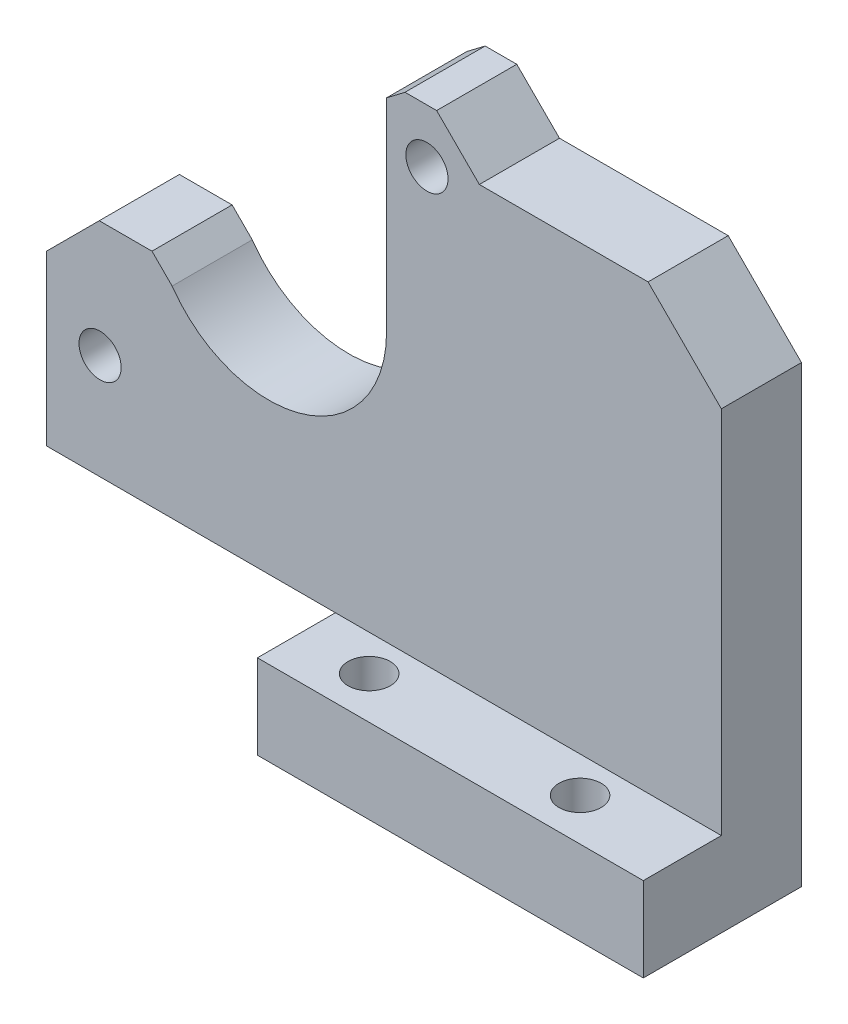
SolidWorks part; units mm, degrees
material "ABS"
ref_plane "Front Plane" through (0, 0, 0) normal (0, 0, 1) x (1, 0, 0)
ref_plane "Top Plane" through (0, 0, 0) normal (0, 1, 0) x (1, 0, 0)
ref_plane "Right Plane" through (0, 0, 0) normal (1, 0, 0) x (0, 0, -1)
sketch "Sketch1" plane through (0, 0, 0) normal (0, 0, 1) x (1, 0, 0)
  line L3 (57.05, 42) -> (41.05, 42)
  line L4 (41.05, 42) -> (37, 46.05)
  line L5 (37, 46.05) -> (34, 46.05)
  line L6 (34, 46.05) -> (32.25, 44.7181)
  line L7 (32.25, 44.7181) -> (32.25, 25.4681)
  line L8 (11.91, 19.09) -> (10, 21)
  line L9 (10, 21) -> (5, 21)
  line L10 (5, 21) -> (0, 16)
  line L14 (0, 0) -> (0, 16)
  line L21 (64, -8) -> (64, 35.05)
  line L22 (57.05, 42) -> (64, 35.05)
  line L26 (0, 0) -> (27.4, 0)
  line L27 (27.4, 0) -> (27.4, -8)
  line L28 (27.4, -8) -> (64, -8)
  arc A0 (32.25, 25.4681) -> (11.91, 19.09) centre (21.08, 25.4681) cw
  dimension "D11" = 5
  dimension "D8" = 21.08
  dimension "D16" = 11.17
  dimension "D2" = 16
  dimension "D3" = 5
  dimension "D4" = 5
  dimension "D5" = 3
  dimension "D6" = 19.25
  dimension "D7" = 8
  dimension "D9" = 6.95
  dimension "D10" = 16
  dimension "D12" = 4.05
  dimension "D13" = 27.4
  dimension "D14" = 36.6
  dimension "D15" = 50
  dimension "D17" = 1.91
  dimension "D18" = 6.95
  dimension "D19" = 4.05
  dimension "D20" = 1.91
extrude "Boss-Extrude1" add sketch "Sketch1" along normal blind 7.6
sketch "Sketch2" plane through (0, 0, 7.6) normal (0, 0, 1) x (1, 0, 0)
  line L1 (64, 0) -> (27.4, 0)
  line L2 (64, 0) -> (64, -8)
  line L3 (64, -8) -> (27.4, -8)
  line L4 (27.4, 0) -> (27.4, -8)
  dimension "D1" = 8
extrude "Boss-Extrude2" add sketch "Sketch2" along normal blind 7.4
sketch "Sketch3" plane through (0, 0, 0) normal (0, 1, 0) x (1, 0, 0)
  line L0 (27.4, -15) -> (27.4, -7.6) construction
  line L3 (64, -15) -> (27.4, -15) construction
  circle A0 centre (54, -11) radius 2
  circle A1 centre (34, -11) radius 2
  point P6 (27.4, -11.3)
  dimension "D1" = 6.6
  dimension "D2" = 4
  dimension "D3" = 20
  dimension "D4" = 4
extrude "Cut-Extrude1" cut sketch "Sketch3" against normal through all
sketch "Sketch4" plane through (0, 0, 7.6) normal (0, 0, 1) x (1, 0, 0)
  circle A0 centre (5.08, 9.9681) radius 2
  circle A1 centre (36.08, 40.9681) radius 2
  arc A2 (11.91, 19.09) -> (32.25, 25.4681) centre (21.08, 25.4681) ccw construction
  dimension "D1" = 16
  dimension "D2" = 31
  dimension "D3" = 15.5
  dimension "D4" = 15.5
  dimension "D5" = 4
extrude "Cut-Extrude2" cut sketch "Sketch4" against normal through all
